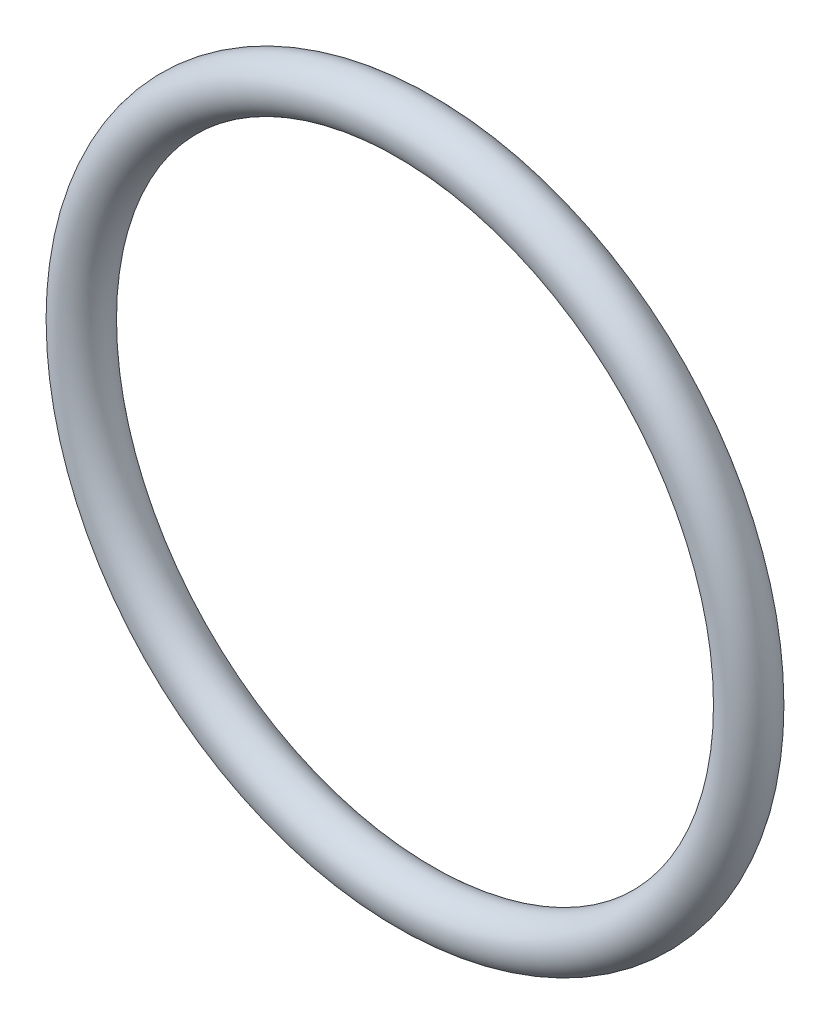
SolidWorks part; units mm, degrees
material "NBR"
ref_plane "Front Plane" through (0, 0, 0) normal (0, 0, 1) x (1, 0, 0)
ref_plane "Top Plane" through (0, 0, 0) normal (0, 1, 0) x (1, 0, 0)
ref_plane "Right Plane" through (0, 0, 0) normal (1, 0, 0) x (0, 0, -1)
sketch "Sketch1" plane through (0, 0, 0) normal (1, 0, 0) x (0, 0, -1)
  line L0 (-151.1552, 0) -> (-75.3028, 0) construction
  circle A0 centre (0, 11.9062) radius 0.7937 construction
  circle A1 centre (0, 11.9062) radius 0.889
  dimension "D3" = 1.778
  dimension "D1" = 22.225
  dimension "D2" = 25.4
revolve "Revolve1" add sketch "Sketch1" angle 360 about L0
